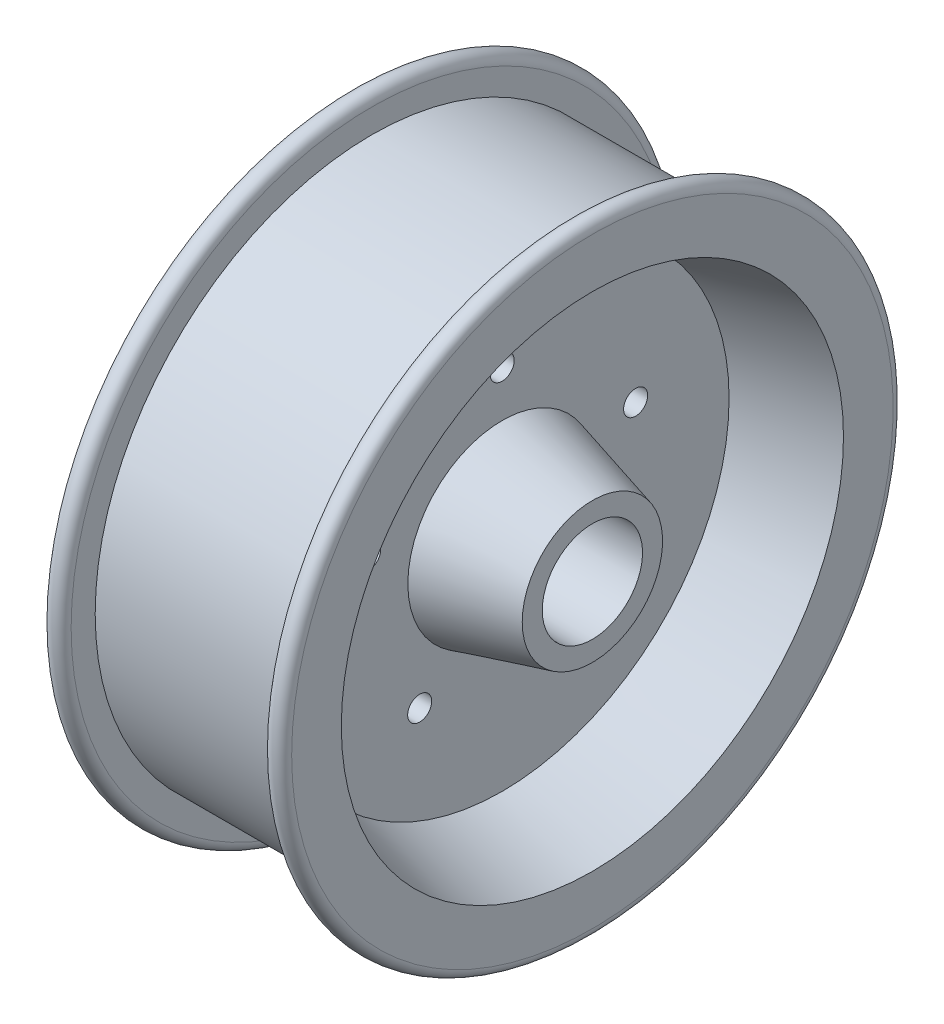
SolidWorks part; units mm, degrees
ref_plane "Front Plane" through (0, 0, 0) normal (0, 0, 1) x (1, 0, 0)
ref_plane "Top Plane" through (0, 0, 0) normal (0, 1, 0) x (1, 0, 0)
ref_plane "Right Plane" through (0, 0, 0) normal (1, 0, 0) x (0, 0, -1)
sketch "Sketch1" plane through (0, 0, 0) normal (0, 0, 1) x (1, 0, 0)
  line L0 (-74.7677, 0) -> (90.2368, 0) construction
  line L1 (0, 86.0831) -> (0, -75.1974) construction
  line L2 (-38.1, 15.875) -> (38.1, 15.875)
  line L3 (38.1, 15.875) -> (38.1, 22.225)
  line L4 (38.1, 22.225) -> (9.525, 29.8816)
  line L5 (9.525, 29.8816) -> (9.525, 71.8708)
  line L6 (9.525, 71.8708) -> (38.1, 79.5274)
  line L7 (38.1, 79.5274) -> (38.1, 95.25)
  line L8 (31.75, 95.25) -> (31.75, 87.63)
  line L9 (31.75, 87.63) -> (-31.75, 87.63)
  line L10 (-31.75, 95.25) -> (-31.75, 87.63)
  line L11 (-38.1, 79.5274) -> (-38.1, 95.25)
  line L12 (-9.525, 71.8708) -> (-38.1, 79.5274)
  line L13 (-9.525, 29.8816) -> (-9.525, 71.8708)
  line L14 (-38.1, 22.225) -> (-9.525, 29.8816)
  line L15 (-38.1, 15.875) -> (-38.1, 22.225)
  arc A0 (38.1, 95.25) -> (31.75, 95.25) centre (34.925, 95.25) ccw
  arc A1 (-38.1, 95.25) -> (-31.75, 95.25) centre (-34.925, 95.25) cw
  point P5 (-31.75, 91.44)
  point P20 (0, 87.63)
  point P25 (0, 15.875)
  dimension "D1" = 76.2
  dimension "D2" = 98.425
  dimension "D3" = 6.35
  dimension "D4" = 15.875
  dimension ".25" = 6.35
  dimension "D5" = 63.5
  dimension "D6" = 87.63
  dimension "D7" = 57.3024
  dimension "D8" = 15
  dimension "D9" = 15
  dimension "D10" = 19.05
revolve "Revolve1" add sketch "Sketch1" angle 360 about L0
sketch "Sketch2" plane through (9.525, 0, 0) normal (1, 0, 0) x (0, 0, -1)
  circle A0 centre (0, 0) radius 44.45 construction
  circle A1 centre (0, 44.45) radius 3.81
  circle A2 centre (42.2745, 13.7358) radius 3.81
  circle A3 centre (26.1271, -35.9608) radius 3.81
  circle A4 centre (-26.1271, -35.9608) radius 3.81
  circle A5 centre (-42.2745, 13.7358) radius 3.81
  point P5 (-31.7992, -41.3638)
  point P6 (0, 0)
  point P7 (0, 0)
  point P16 (0, 0)
  point P17 (0, 0)
  point P18 (0, 0)
  dimension "D1" = 88.9
  dimension "D2" = 7.62
  dimension "D3" = 5
extrude "Cut-Extrude1" cut sketch "Sketch2" against normal through all
